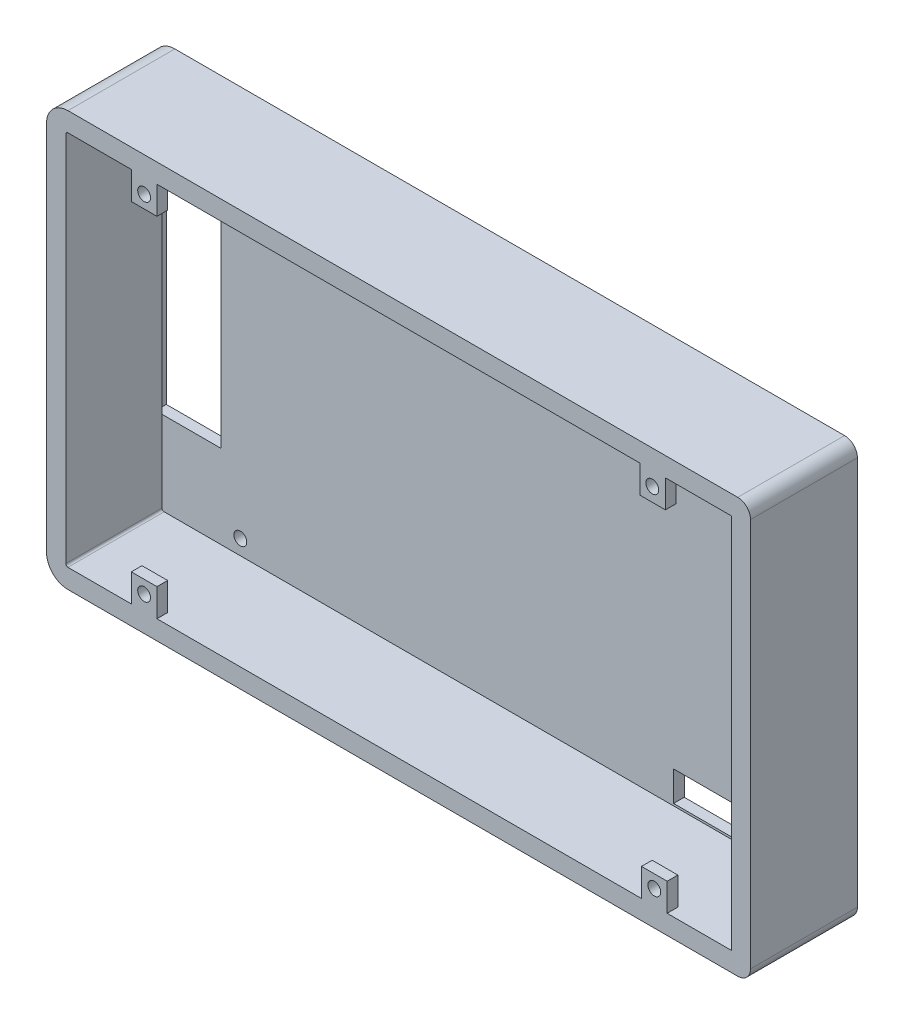
SolidWorks part; units mm, degrees
ref_plane "Alzado" through (0, 0, 0) normal (0, 0, 1) x (1, 0, 0)
ref_plane "Planta" through (0, 0, 0) normal (0, 1, 0) x (1, 0, 0)
ref_plane "Vista lateral" through (0, 0, 0) normal (1, 0, 0) x (0, 0, -1)
sketch "Croquis1" plane through (0, 0, 0) normal (0, 0, 1) x (1, 0, 0)
  line L0 (92.8154, 92) -> (92.8154, 5)
  line L2 (-68.8143, 24) -> (-53.5, 24) construction
  line L3 (-68.8143, 72.9995) -> (-68.8143, 24) construction
  line L4 (-53.5, 72.9995) -> (-68.8143, 72.9995) construction
  line L5 (-53.5, 24) -> (-53.5, 72.9995) construction
  line L6 (-68.8143, 24) -> (-53.5, 24)
  line L7 (-68.8143, 72.9995) -> (-68.8143, 24)
  line L8 (-53.5, 72.9995) -> (-68.8143, 72.9995)
  line L9 (-53.5, 24) -> (-53.5, 72.9995)
  line L11 (26.9383, 87.6693) -> (5.8322, 87.6693)
  line L12 (26.9383, 87.6693) -> (26.9383, 92)
  line L13 (26.9383, 92) -> (5.8322, 92)
  line L14 (5.8322, 87.6693) -> (5.8322, 92)
  line L15 (66.9049, 92) -> (51.9049, 92)
  line L16 (66.9049, 92) -> (66.9049, 85)
  line L17 (66.9049, 85) -> (51.9049, 85)
  line L18 (51.9049, 92) -> (51.9049, 85)
  line L19 (67.3154, 5) -> (52.3154, 5)
  line L20 (-52, 11) -> (-52, 86)
  line L21 (-52, 86) -> (-46, 86)
  line L22 (-46, 86) -> (-46, 92)
  line L23 (-46, 92) -> (66.9049, 92)
  line L24 (66.9049, 92) -> (66.9049, 86)
  line L25 (66.9049, 86) -> (72.9049, 86)
  line L26 (72.9049, 86) -> (72.9049, 92)
  line L27 (72.9049, 92) -> (92.8154, 92)
  line L28 (92.8154, 92) -> (92.8154, 97)
  line L29 (92.8154, 97) -> (-66.8143, 97)
  line L30 (-71.8143, 92) -> (-71.8143, 5)
  line L31 (-66.8143, 0) -> (92.8154, 0)
  line L32 (92.8154, 0) -> (92.8154, 5)
  line L33 (92.8154, 5) -> (73.3154, 5)
  line L34 (73.3154, 5) -> (73.3154, 11)
  line L35 (73.3154, 11) -> (67.3154, 11)
  line L36 (67.3154, 11) -> (67.3154, 5)
  line L37 (67.3154, 5) -> (-46, 5)
  line L38 (-46, 5) -> (-46, 11)
  line L39 (-46, 11) -> (-52, 11)
  line L48 (92.8154, 92) -> (92.8154, 97)
  line L49 (92.8154, 97) -> (-66.8143, 97)
  line L50 (-71.8143, 92) -> (-71.8143, 5)
  line L51 (-66.8143, 0) -> (92.8154, 0)
  line L52 (92.8154, 0) -> (92.8154, 5)
  line L58 (-46, 5) -> (-46, 11)
  line L59 (-46, 11) -> (-52, 11)
  line L60 (67.3154, 5) -> (67.3154, 12)
  line L61 (67.3154, 12) -> (52.3154, 12)
  line L62 (52.3154, 5) -> (52.3154, 12)
  circle A0 centre (-49, 8) radius 1.5 construction
  circle A1 centre (-49, 89) radius 1.5 construction
  arc A2 (-66.8143, 97) -> (-71.8143, 92) centre (-66.8143, 92) ccw
  arc A3 (-71.8143, 5) -> (-66.8143, 0) centre (-66.8143, 5) ccw
  arc A4 (-66.8143, 97) -> (-71.8143, 92) centre (-66.8143, 92) ccw
  arc A5 (-71.8143, 5) -> (-66.8143, 0) centre (-66.8143, 5) ccw
  circle A6 centre (69.8502, 89.2089) radius 1.5 construction
  circle A7 centre (70.3154, 8) radius 1.5 construction
  circle A8 centre (-49, 8) radius 1.5
  circle A9 centre (-49, 89) radius 1.5
  circle A10 centre (69.8502, 89.2089) radius 1.5
  circle A11 centre (70.3154, 8) radius 1.5
  dimension "D2" = 15
  dimension "D3" = 7
  dimension "D4" = 15
  dimension "D5" = 7
  dimension "D1" = 0
extrude "Saliente-Extruir1" add sketch "Croquis1" along normal blind 2.5
sketch "Croquis2" plane through (0, 0, 2.5) normal (0, 0, 1) x (1, 0, 0)
  line L4 (-71.8143, 92) -> (-71.8143, 5)
  line L5 (-66.8143, 0) -> (92.8154, 0)
  line L6 (92.8154, 0) -> (92.8154, 97)
  line L7 (92.8154, 97) -> (-66.8143, 97)
  line L8 (-71.8143, 92) -> (-71.8143, 5)
  line L9 (-66.8143, 0) -> (92.8154, 0)
  line L10 (92.8154, 0) -> (92.8154, 97)
  line L11 (92.8154, 97) -> (-66.8143, 97)
  line L16 (-67.3143, 92) -> (-67.3143, 5)
  line L17 (-66.8143, 4.5) -> (88.3154, 4.5)
  line L18 (88.3154, 4.5) -> (88.3154, 92.5)
  line L19 (88.3154, 92.5) -> (-66.8143, 92.5)
  line L20 (-67.3143, 92) -> (-67.3143, 5)
  line L21 (-66.8143, 4.5) -> (88.3154, 4.5)
  line L22 (88.3154, 4.5) -> (88.3154, 92.5)
  line L23 (88.3154, 92.5) -> (-66.8143, 92.5)
  arc A2 (-71.8143, 5) -> (-66.8143, 0) centre (-66.8143, 5) ccw
  arc A3 (-66.8143, 97) -> (-71.8143, 92) centre (-66.8143, 92) ccw
  arc A4 (-71.8143, 5) -> (-66.8143, 0) centre (-66.8143, 5) ccw
  arc A5 (-66.8143, 97) -> (-71.8143, 92) centre (-66.8143, 92) ccw
  arc A8 (-67.3143, 5) -> (-66.8143, 4.5) centre (-66.8143, 5) ccw
  arc A9 (-66.8143, 92.5) -> (-67.3143, 92) centre (-66.8143, 92) ccw
  arc A10 (-67.3143, 5) -> (-66.8143, 4.5) centre (-66.8143, 5) ccw
  arc A11 (-66.8143, 92.5) -> (-67.3143, 92) centre (-66.8143, 92) ccw
  dimension "D1" = 0
  dimension "D2" = 4.5
extrude "Saliente-Extruir2" add sketch "Croquis2" along normal blind 25.5
sketch "Croquis3" plane through (0, 4.5, 0) normal (0, 1, 0) x (1, 0, 0)
  line L0 (-66.8143, -28) -> (-66.8143, 0) construction
  line L1 (88.3154, -28) -> (-66.8143, -28)
  line L2 (88.3154, -28) -> (88.3154, -26)
  line L3 (88.3154, -26) -> (-66.8143, -26)
  line L4 (-66.8143, -28) -> (-66.8143, -26)
  dimension "D1" = 2
extrude "Saliente-Extruir3" add sketch "Croquis3" along normal up to next
fillet "Redondeo1" radius 3 2 edges at (92.8154, 0, 14) (92.8154, 97, 14)
fillet "Redondeo2" radius 3 8 edges at (91.9367, 0.8787, 28) (-70.3498, 1.4645, 28) (11.5006, 0, 28) (-71.8143, 48.5, 28) (-70.3498, 95.5355, 28) (91.9367, 96.1213, 28) (92.8154, 48.5, 28) (11.5006, 97, 28)
sketch "Croquis6" plane through (0, 0, 0) normal (0, -1, 0) x (-1, 0, 0)
  line L1 (-92.8154, -25) -> (79.2185, -25)
  line L2 (-92.8154, -25) -> (-92.8154, -29.9488)
  line L3 (-92.8154, -29.9488) -> (79.2185, -29.9488)
  line L4 (79.2185, -25) -> (79.2185, -29.9488)
extrude "Cortar-Extruir3" cut sketch "Croquis6" against normal blind 114.5
sketch "Croquis7" plane through (0, 0, 25) normal (0, 0, 1) x (1, 0, 0)
  line L0 (88.3154, 4.5) -> (-66.8143, 4.5) construction
  line L1 (67.3154, 4.5) -> (73.3154, 4.5)
  line L2 (67.3154, 4.5) -> (67.3154, 11)
  line L3 (67.3154, 11) -> (73.3154, 11)
  line L4 (-71.8143, 92) -> (-71.8143, 5)
  line L5 (-66.8143, 0) -> (89.8154, 0)
  line L6 (92.8154, 3) -> (92.8154, 94)
  line L7 (89.8154, 97) -> (-66.8143, 97)
  line L8 (-71.8143, 92) -> (-71.8143, 5)
  line L9 (-66.8143, 0) -> (89.8154, 0)
  line L10 (92.8154, 3) -> (92.8154, 94)
  line L11 (89.8154, 97) -> (-66.8143, 97)
  line L12 (73.3154, 4.5) -> (73.3154, 11)
  line L13 (70.3154, 8) -> (70.3154, 4.5) construction
  line L14 (-49, 8) -> (-49, 4.5) construction
  line L15 (-46, 4.5) -> (-52, 4.5)
  line L16 (-46, 4.5) -> (-46, 11)
  line L17 (-46, 11) -> (-52, 11)
  line L18 (-52, 4.5) -> (-52, 11)
  line L19 (-66.8143, 92.5) -> (88.3154, 92.5) construction
  line L20 (-46, 92.5) -> (-52, 92.5)
  line L21 (-46, 92.5) -> (-46, 86)
  line L22 (-46, 86) -> (-52, 86)
  line L23 (-52, 92.5) -> (-52, 86)
  line L24 (-49, 89) -> (-49, 92.5) construction
  line L32 (66.9088, 92.5) -> (72.9088, 92.5)
  line L33 (66.9088, 92.5) -> (66.9088, 86)
  line L34 (66.9088, 86) -> (72.9088, 86)
  line L35 (72.9088, 92.5) -> (72.9088, 86)
  circle A0 centre (-49, 8) radius 1.5 construction
  circle A1 centre (-49, 89) radius 1.5 construction
  circle A2 centre (69.8502, 89.2089) radius 1.5 construction
  circle A3 centre (70.3154, 8) radius 1.5 construction
  arc A4 (-71.8143, 5) -> (-66.8143, 0) centre (-66.8143, 5) ccw
  arc A5 (89.8154, 0) -> (92.8154, 3) centre (89.8154, 3) ccw
  arc A6 (92.8154, 94) -> (89.8154, 97) centre (89.8154, 94) ccw
  arc A7 (-66.8143, 97) -> (-71.8143, 92) centre (-66.8143, 92) ccw
  arc A8 (-71.8143, 5) -> (-66.8143, 0) centre (-66.8143, 5) ccw
  arc A9 (89.8154, 0) -> (92.8154, 3) centre (89.8154, 3) ccw
  arc A10 (92.8154, 94) -> (89.8154, 97) centre (89.8154, 94) ccw
  arc A11 (-66.8143, 97) -> (-71.8143, 92) centre (-66.8143, 92) ccw
  circle A12 centre (-49, 8) radius 1.5
  circle A13 centre (-49, 89) radius 1.5
  circle A14 centre (69.8502, 89.2089) radius 1.5
  circle A15 centre (70.3154, 8) radius 1.5
  point P30 (70.3154, 4.5)
  point P36 (-49, 4.5)
  point P44 (-49, 92.5)
  line M18 (88.3154, 4.5) -> (-66.8143, 4.5)
  line M22 (-66.8143, 92.5) -> (88.3154, 92.5)
  dimension "D2" = 6.5
  dimension "D3" = 6
  dimension "D4" = 0
  dimension "D5" = 6
  dimension "D6" = 6.5
  dimension "D7" = 0
  dimension "D8" = 6
  dimension "D9" = 6.5
  dimension "D10" = 0
  dimension "D11" = 6
  dimension "D1" = 0
extrude "Saliente-Extruir4" add sketch "Croquis7" against normal blind 2.5 contours L35 L33 L34 A14 M22 | L23 L22 L21 A13 M22 | L12 L3 L2 A15 M18 | L18 L16 L17 A12 M18
